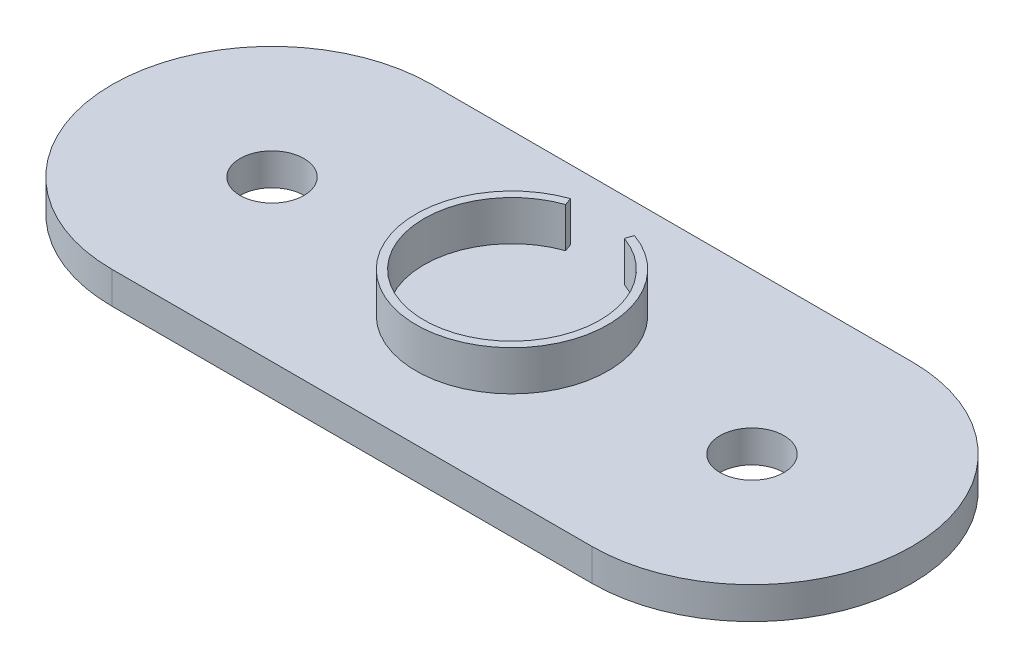
SolidWorks part; units mm, degrees
ref_plane "前视基准面" through (0, 0, 0) normal (0, 0, 1) x (1, 0, 0)
ref_plane "上视基准面" through (0, 0, 0) normal (0, 1, 0) x (1, 0, 0)
ref_plane "右视基准面" through (0, 0, 0) normal (1, 0, 0) x (0, 0, -1)
sketch "草图1" plane through (0, 0, 0) normal (0, 1, 0) x (1, 0, 0)
  line L0 (0, 0) -> (30, 0) construction
  line L1 (0, 10) -> (30, 10)
  line L2 (0, -10) -> (30, -10)
  arc A0 (0, 10) -> (0, -10) centre (0, 0) ccw
  arc A1 (30, -10) -> (30, 10) centre (30, 0) ccw
  point P3 (15, 0)
  dimension "D2" = 10
  dimension "D1" = 30
extrude "凸台-拉伸1" add sketch "草图1" along normal blind 2
sketch "草图2" plane through (0, 2, 0) normal (0, 1, 0) x (1, 0, 0)
  circle A0 centre (0, 0) radius 2
  circle A1 centre (30, 0) radius 2
  dimension "D1" = 4
extrude "切除-拉伸1" cut sketch "草图2" against normal blind 2
sketch "草图3" plane through (0, 2, 0) normal (0, 1, 0) x (1, 0, 0)
  circle A0 centre (15, 0) radius 6
  circle A1 centre (15, 0) radius 5.5
  dimension "D1" = 12
  dimension "D2" = 11
extrude "凸台-拉伸2" add sketch "草图3" along normal blind 2.5
sketch "草图4" plane through (0, 2, 0) normal (0, 1, 0) x (1, 0, 0)
  line L0 (15, 0) -> (13, 5.6569)
  line L1 (15, 0) -> (17, 5.6569)
  line L2 (13, 5.6569) -> (17, 5.6569) construction
  arc A0 (17, 5.6569) -> (13, 5.6569) centre (15, 0) ccw
  circle A1 centre (15, 0) radius 6 construction
  dimension "D1" = 4
extrude "切除-拉伸2" cut sketch "草图4" along normal blind 2.5
